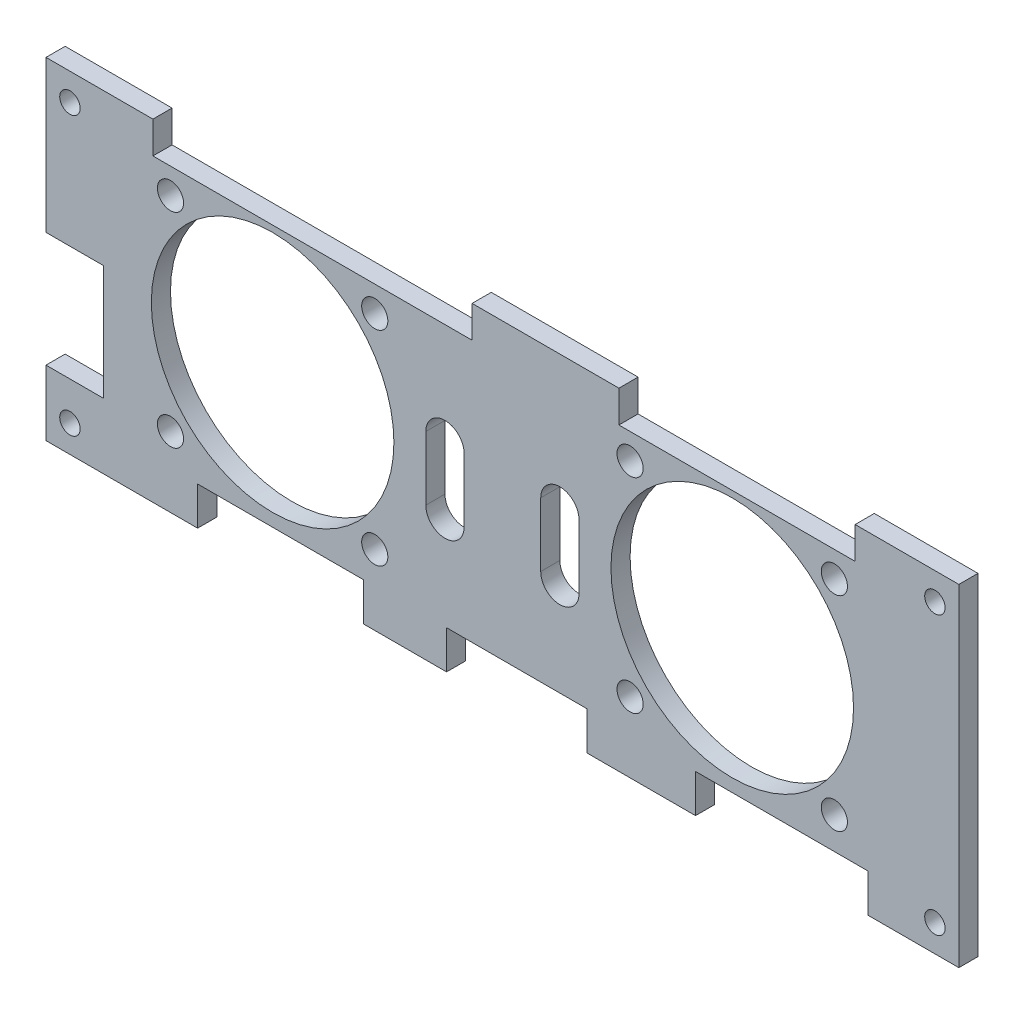
SolidWorks part; units mm, degrees
ref_plane "Front Plane" through (0, 0, 0) normal (0, 0, 1) x (1, 0, 0)
ref_plane "Top Plane" through (0, 0, 0) normal (0, 1, 0) x (1, 0, 0)
ref_plane "Right Plane" through (0, 0, 0) normal (1, 0, 0) x (0, 0, -1)
sketch "Sketch1" plane through (0, 0, 0) normal (0, 0, 1) x (1, 0, 0)
  line L1 (-71.5, 26) -> (71.5, 26)
  line L2 (-71.5, 26) -> (-71.5, -26)
  line L3 (-71.5, -26) -> (71.5, -26)
  line L4 (71.5, 26) -> (71.5, -26)
  line L5 (-71.5, 26) -> (71.5, -26) construction
  line L6 (-71.5, -26) -> (71.5, 26) construction
  line L7 (-67.75, -21.75) -> (67.75, -21.75) construction
  line L8 (-67.75, -21.75) -> (-67.75, 21.75) construction
  line L9 (-67.75, 21.75) -> (67.75, 21.75) construction
  line L10 (67.75, -21.75) -> (67.75, 21.75) construction
  line L11 (-67.75, -21.75) -> (67.75, 21.75) construction
  line L12 (-67.75, 21.75) -> (67.75, -21.75) construction
  circle A0 centre (-67.75, 21.75) radius 1.6
  circle A1 centre (-67.75, -21.75) radius 1.6
  circle A2 centre (67.75, 21.75) radius 1.6
  circle A3 centre (67.75, -21.75) radius 1.6
  point P0 (0, 0)
  point P5 (0, 0)
  dimension "D5" = 3.2
  dimension "D1" = 143
  dimension "D2" = 52
  dimension "D3" = 43.5
  dimension "D4" = 135.5
extrude "Boss-Extrude1" add sketch "Sketch1" along normal blind 3
sketch "Sketch2" plane through (0, 0, 3) normal (0, 0, 1) x (1, 0, 0)
  line L0 (-71.5, 2.25) -> (-62.5, 2.25)
  line L1 (-47.75, -20) -> (-21.75, -20)
  line L2 (-47.75, -20) -> (-47.75, -26)
  line L4 (-21.75, -20) -> (-21.75, -26)
  line L5 (-71.5, -26) -> (71.5, -26) construction
  line L6 (-47.75, -26) -> (57.25, -26)
  line L7 (-71.5, 26) -> (-71.5, -26) construction
  line L8 (-8.75, -20) -> (13.25, -20)
  line L9 (-8.75, -20) -> (-8.75, -26)
  line L11 (13.25, -20) -> (13.25, -26)
  line L12 (-62.5, 2.25) -> (-62.5, -15.75)
  line L13 (-62.5, -15.75) -> (-71.5, -15.75)
  line L14 (30.25, -20) -> (57.25, -20)
  line L15 (30.25, -20) -> (30.25, -26)
  line L17 (57.25, -20) -> (57.25, -26)
  line L18 (-71.5, 2.25) -> (-71.5, -15.75)
  circle A0 centre (-67.75, -21.75) radius 1.6 construction
  line M17 (-71.5, 26) -> (-71.5, -26)
  line M18 (-71.5, -26) -> (71.5, -26)
  dimension "D1" = 20
  dimension "D2" = 13
  dimension "D3" = 17
  dimension "D4" = 26
  dimension "D5" = 22
  dimension "D6" = 27
  dimension "D7" = 6
  dimension "D8" = 9
  dimension "D9" = 18
  dimension "D10" = 6
extrude "Cut-Extrude1" cut sketch "Sketch2" against normal blind 10 and the other way through all contours L4 L1 L2 M18 | L11 L8 L9 L6 | L17 L14 L15 L6 | L13 L12 L0 M17
sketch "Sketch4" plane through (0, 0, 3) normal (0, 0, 1) x (1, 0, 0)
  line L0 (71.5, 26) -> (-71.5, 26) construction
  line L1 (-54.75, 26) -> (-4.75, 26)
  line L2 (-54.75, 26) -> (-54.75, 21)
  line L3 (-54.75, 21) -> (-4.75, 21)
  line L4 (-4.75, 26) -> (-4.75, 21)
  line L6 (18.25, 26) -> (55.25, 26)
  line L7 (18.25, 26) -> (18.25, 21)
  line L8 (18.25, 21) -> (55.25, 21)
  line L9 (55.25, 26) -> (55.25, 21)
  line L10 (11.5, 14.5) -> (30.5, 14.5)
  line L11 (11.5, 14.5) -> (11.5, 6.5)
  line L12 (11.5, 6.5) -> (30.5, 6.5)
  line L13 (30.5, 14.5) -> (30.5, 6.5)
  circle A0 centre (-67.75, 21.75) radius 1.6 construction
  circle A1 centre (67.75, 21.75) radius 1.6 construction
  dimension "D3" = 13
  dimension "D1" = 5
  dimension "D2" = 50
  dimension "D4" = 23
  dimension "D5" = 37
  dimension "D6" = 8
  dimension "D7" = 19
  dimension "D8" = 37.25
  dimension "D9" = 11.5
extrude "Cut-Extrude2" cut sketch "Sketch4" against normal blind 3 contours L7 L6 L9 L8 | L2 L1 L4 L3
sketch "Sketch5" plane through (0, 0, 3) normal (0, 0, 1) x (1, 0, 0)
  line L1 (52, -15) -> (20, -15) construction
  line L2 (52, -15) -> (52, 17) construction
  line L3 (52, 17) -> (20, 17) construction
  line L4 (20, -15) -> (20, 17) construction
  line L5 (52, -15) -> (20, 17) construction
  line L6 (52, 17) -> (20, -15) construction
  line L7 (18.25, 21) -> (55.25, 21) construction
  line L9 (56, -19) -> (16, -19) construction
  line L10 (56, -19) -> (56, 21) construction
  line L11 (56, 21) -> (16, 21) construction
  line L12 (16, -19) -> (16, 21) construction
  line L13 (56, -19) -> (16, 21) construction
  line L14 (56, 21) -> (16, -19) construction
  circle A0 centre (52, -15) radius 2.05
  circle A1 centre (20, -15) radius 2.05
  circle A2 centre (20, 17) radius 2.05
  circle A3 centre (52, 17) radius 2.05
  circle A4 centre (36, 1) radius 19
  point P0 (36, 1)
  point P9 (36, 1)
  dimension "D2" = 4.1
  dimension "D3" = 20
  dimension "D6" = 38
  dimension "D1" = 32
  dimension "D4" = 4
  dimension "D5" = 40
extrude "Cut-Extrude3" cut sketch "Sketch5" against normal blind 3
mirror "Mirror1" about plane through (0, 0, 0) normal (1, 0, 0) of "Cut-Extrude3"
sketch "Sketch6" plane through (0, 0, 3) normal (0, 0, 1) x (1, 0, 0)
  line L0 (9, -5) -> (9, 5) construction
  line L1 (6, -5) -> (6, 5)
  line L2 (12, -5) -> (12, 5)
  line L3 (0, 0) -> (0, 7.0805) construction
  line L4 (-9, -5) -> (-9, 5) construction
  line L5 (-6, -5) -> (-6, 5)
  line L6 (-12, -5) -> (-12, 5)
  arc A0 (6, -5) -> (12, -5) centre (9, -5) ccw
  arc A1 (12, 5) -> (6, 5) centre (9, 5) ccw
  arc A2 (-6, -5) -> (-12, -5) centre (-9, -5) cw
  arc A3 (-12, 5) -> (-6, 5) centre (-9, 5) cw
  point P2 (9, 0)
  point P12 (-9, 0)
  dimension "D2" = 3
  dimension "D1" = 10
  dimension "D3" = 9
extrude "Cut-Extrude4" cut sketch "Sketch6" against normal blind 3
